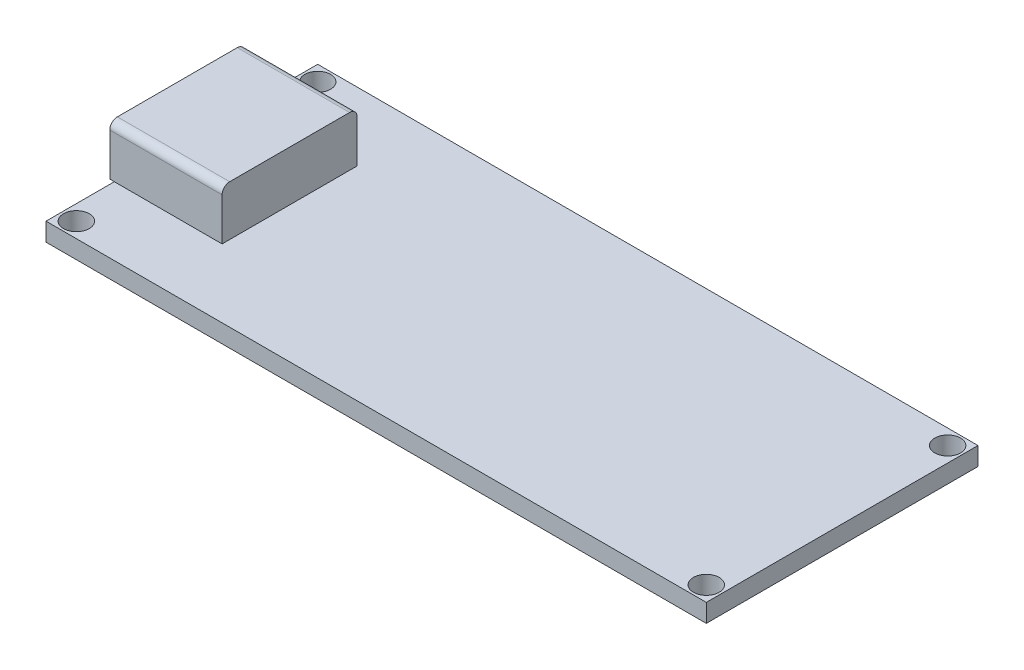
SolidWorks part; units mm, degrees
ref_plane "Front Plane" through (0, 0, 0) normal (0, 0, 1) x (1, 0, 0)
ref_plane "Top Plane" through (0, 0, 0) normal (0, 1, 0) x (1, 0, 0)
ref_plane "Right Plane" through (0, 0, 0) normal (1, 0, 0) x (0, 0, -1)
sketch "Sketch1" plane through (0, 0, 0) normal (0, 1, 0) x (1, 0, 0)
  line L0 (-21.75, 8.95) -> (21.75, -8.95) construction
  line L1 (-21.75, -8.95) -> (21.75, -8.95)
  line L2 (-21.75, -8.95) -> (-21.75, 8.95)
  line L3 (-21.75, 8.95) -> (21.75, 8.95)
  line L4 (21.75, -8.95) -> (21.75, 8.95)
  line L5 (-20.75, 7.95) -> (20.75, 7.95) construction
  line L6 (20.75, 7.95) -> (20.75, -7.95) construction
  line L7 (20.75, -7.95) -> (-20.75, -7.95) construction
  line L8 (-20.75, -7.95) -> (-20.75, 7.95) construction
  circle A0 centre (-20.75, 7.95) radius 0.85
  circle A1 centre (20.75, -7.95) radius 0.85
  circle A2 centre (20.75, 7.95) radius 0.85
  circle A3 centre (-20.75, -7.95) radius 0.85
  point P4 (0, 0)
  point P15 (-20.565, -7.95)
  dimension "D3" = 1.7
  dimension "D4" = 1
  dimension "D5" = 1
  dimension "D1" = 43.5
  dimension "D2" = 17.9
  dimension "D6" = 1
  dimension "D7" = 1
extrude "Boss-Extrude1" add sketch "Sketch1" along normal blind 1.2
sketch "Sketch2" plane through (0, 1.2, 0) normal (0, 1, 0) x (1, 0, 0)
  line L0 (-21.75, 0) -> (-22.05, 0) construction
  line L1 (-22.05, 4.45) -> (-14.65, 4.45)
  line L2 (-22.05, 4.45) -> (-22.05, -4.45)
  line L3 (-22.05, -4.45) -> (-14.65, -4.45)
  line L4 (-14.65, 4.45) -> (-14.65, -4.45)
  line L5 (-21.75, 8.95) -> (-21.75, -8.95) construction
  dimension "D1" = 8.9
  dimension "D2" = 7.4
  dimension "D3" = 0.3
extrude "Boss-Extrude2" add sketch "Sketch2" along normal blind 3.3
fillet "Fillet1" radius 0.5 2 edges at (-18.35, 4.5, -4.45) (-18.35, 4.5, 4.45)
